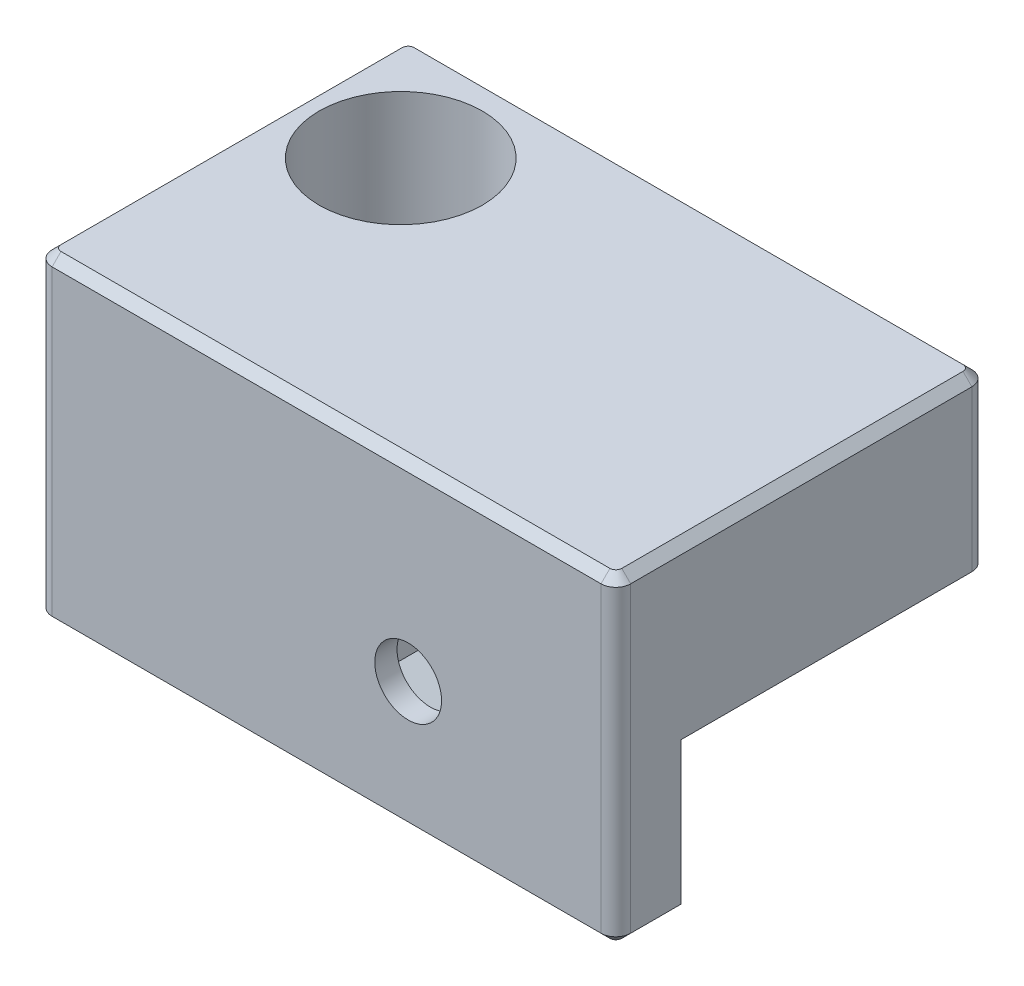
SolidWorks part; units mm, degrees
ref_plane "Front Plane" through (0, 0, 0) normal (0, 0, 1) x (1, 0, 0)
ref_plane "Top Plane" through (0, 0, 0) normal (0, 1, 0) x (1, 0, 0)
ref_plane "Right Plane" through (0, 0, 0) normal (1, 0, 0) x (0, 0, -1)
sketch "Sketch1" plane through (0, 0, 0) normal (0, 0, 1) x (1, 0, 0)
  line L0 (0, 0) -> (0, 21.6)
  line L1 (0, 21.6) -> (39, 21.6)
  line L3 (35, 17.6) -> (15, 17.6)
  line L4 (15, 17.6) -> (15, 0)
  line L5 (15, 0) -> (0, 0)
  line L8 (39, 21.6) -> (39, 9.6)
  line L9 (39, 9.6) -> (35, 9.6)
  line L10 (35, 17.6) -> (35, 9.6)
  dimension "D1" = 20
  dimension "D2" = 17.6
  dimension "D3" = 4
  dimension "D4" = 15
  dimension "D5" = 4
  dimension "D6" = 8
extrude "Boss-Extrude1" add sketch "Sketch1" along normal mid plane 15
hole_wizard "CBORE for M6 Hex Socket Head Cap Screw1" positions "Sketch4" profile "Sketch3" counterbore size "M6" standard "DIN" end condition through all
sketch "Sketch4" plane through (0, 21.6, 0) normal (0, 1, 0) x (1, 0, 0)
  point P0 (7, 0)
  dimension "D1" = 7
sketch "Sketch3" plane through (7, 21.6, 0) normal (1, 0, 0) x (0, 0, 1)
  line L0 (0, 0) -> (0, 21.6)
  line L1 (0, 21.6) -> (3.3, 21.6)
  line L3 (3.3, 21.6) -> (3.3, 9)
  line L4 (3.3, 9) -> (5.5, 9)
  line L5 (5.5, 9) -> (5.5, 0)
  line L7 (5.5, 0) -> (0, 0)
  line L11 (0, -6.35) -> (0, 107.95) construction
  dimension "Thru Hole Dia." = 6.6
  dimension "Thru Hole Depth" = 21.6
  dimension "C'Bore Dia." = 11
  dimension "C'Bore Depth" = 9
sketch "Sketch5" plane through (0, 0, 7.5) normal (0, 0, 1) x (1, 0, 0)
  line L8 (0, 0) -> (15, 0)
  line L9 (15, 0) -> (15, 17.6)
  line L10 (15, 17.6) -> (35, 17.6)
  line L11 (35, 17.6) -> (35, 9.6)
  line L12 (35, 9.6) -> (39, 9.6)
  line L13 (39, 9.6) -> (39, 21.6)
  line L14 (39, 21.6) -> (0, 21.6)
  line L15 (0, 21.6) -> (0, 0)
  line L16 (0, 0) -> (15, 0)
  line L17 (15, 0) -> (15, 17.6)
  line L18 (15, 17.6) -> (35, 17.6)
  line L19 (35, 17.6) -> (35, 9.6)
  line L20 (35, 9.6) -> (39, 9.6)
  line L21 (39, 9.6) -> (39, 21.6)
  line L22 (39, 21.6) -> (0, 21.6)
  line L23 (0, 21.6) -> (0, 0)
  dimension "D1" = 0
extrude "Boss-Extrude2" add sketch "Sketch5" along normal blind 5
sketch "Sketch6" plane through (0, 0, 12.5) normal (0, 0, 1) x (1, 0, 0)
  line L1 (0, 21.6) -> (39, 21.6)
  line L2 (0, 21.6) -> (0, 0)
  line L3 (0, 0) -> (39, 0)
  line L4 (39, 21.6) -> (39, 0)
  point P5 (39, 21.6)
  point P7 (0, 0)
extrude "Boss-Extrude3" add sketch "Sketch6" along normal blind 5
sketch "Sketch7" plane through (0, 0, 12.5) normal (0, 0, -1) x (-1, 0, 0)
  line L0 (-25, 17.6) -> (-25, 8.8) construction
  line L1 (-25, 4.7585) -> (-21.5, 6.7793)
  line L2 (-21.5, 6.7793) -> (-21.5, 10.8207)
  line L3 (-21.5, 10.8207) -> (-25, 12.8415)
  line L4 (-25, 12.8415) -> (-28.5, 10.8207)
  line L5 (-28.5, 10.8207) -> (-28.5, 6.7793)
  line L6 (-28.5, 6.7793) -> (-25, 4.7585)
  line L7 (-15, 17.6) -> (-35, 17.6) construction
  line L8 (-25, 8.8) -> (-15, 8.8) construction
  line L9 (-15, 0) -> (-15, 17.6) construction
  circle A0 centre (-25, 8.8) radius 3.5 construction
  dimension "D1" = 7
extrude "Cut-Extrude1" cut sketch "Sketch7" against normal blind 3.5
hole_wizard "M4 Clearance Hole1" positions "Sketch8" profile "Sketch9" hole size "M4" standard "DIN" end condition up to next
sketch "Sketch8" plane through (0, 0, 16) normal (0, 0, -1) x (-1, 0, 0)
  line L0 (-25, 12.8415) -> (-25, 4.7585) construction
  point P7 (-25, 8.8)
sketch "Sketch9" plane through (25, 8.8, 16) normal (1, 0, 0) x (0, 1, 0)
  line L0 (0, 0) -> (0, 1.5)
  line L1 (0, 1.5) -> (2.25, 1.5)
  line L2 (2.25, 1.5) -> (2.25, 0)
  line L5 (2.25, 0) -> (0, 0)
  line L11 (0, -6.35) -> (0, 107.95) construction
  dimension "Thru Hole Dia." = 4.5
  dimension "Thru Hole Depth" = 1.5
fillet "Fillet1" radius 1 5 edges at (0, 10.8, -7.5) (35, 9.6, 2.5) (39, 15.6, -7.5) (39, 10.8, 17.5) (0, 10.8, 17.5)
chamfer "Chamfer1" distance 0.6 angle 45 26 edges at (15, 8.8, -7.5) (39, 21.6, 5) (19.5, 21.6, -7.5) (0.2929, 21.6, -7.2071) (0, 21.6, 5) (25, 17.6, -7.5) (7, 0, 3.3) (0, 0, 5) (0.2929, 0, -7.2071) (8, 0, -7.5) (15, 0, 2.5) (19.5, 0, 17.5) (39, 0, 14.5) (27, 0, 12.5) (19.5, 21.6, 17.5) (38.7071, 21.6, 17.2071) (0.2929, 21.6, 17.2071) (38.7071, 21.6, -7.2071) (38.7071, 0, 17.2071) (0.2929, 0, 17.2071) (35, 14.1, -7.5) (35.2929, 9.8929, -7.5) (37, 9.6, -7.5) (38.7071, 9.6, -7.2071) (39, 9.6, 3) (39, 4.8, 12.5)
